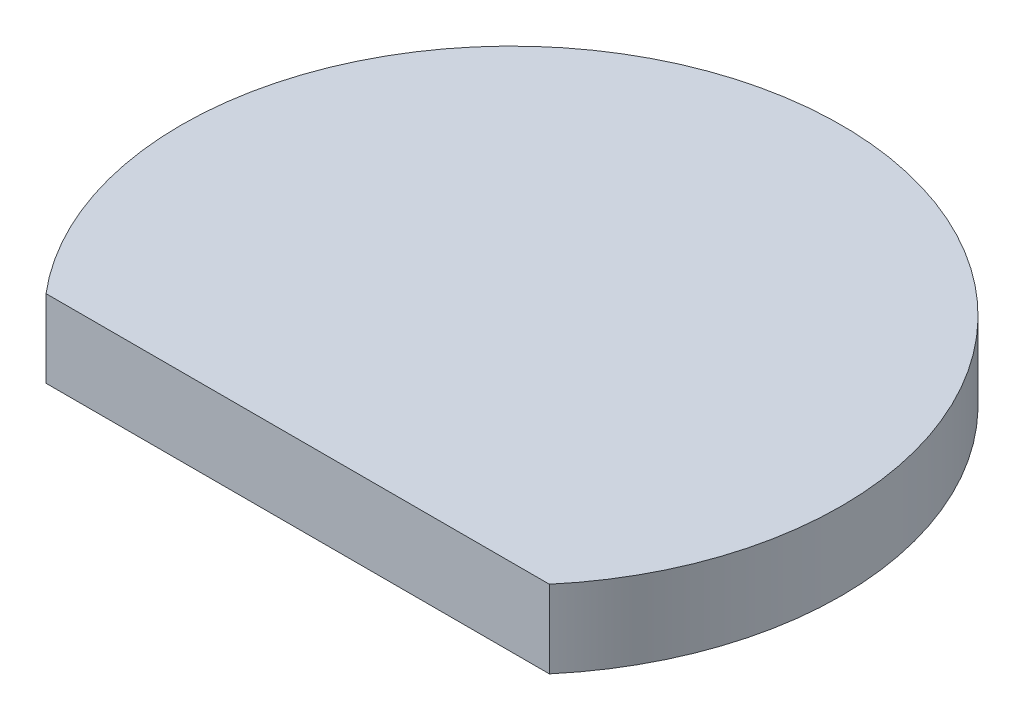
SolidWorks part; units mm, degrees
ref_plane "Płaszczyzna przednia" through (0, 0, 0) normal (0, 0, 1) x (1, 0, 0)
ref_plane "Płaszczyzna górna" through (0, 0, 0) normal (0, 1, 0) x (1, 0, 0)
ref_plane "Płaszczyzna prawa" through (0, 0, 0) normal (1, 0, 0) x (0, 0, -1)
sketch "Szkic1" plane through (0, 0, 0) normal (0, 1, 0) x (1, 0, 0)
  line L0 (-6.4807, -5.5) -> (6.4807, -5.5)
  circle A0 centre (0, 0) radius 5.5
  arc A1 (6.4807, -5.5) -> (-6.4807, -5.5) centre (0, 0) ccw
  point P7 (0, -5.5)
  dimension "D1" = 11
  dimension "D2" = 17
extrude "Dodanie-wyciągnięcie1" add sketch "Szkic1" along normal blind 2 contours A1 L0
